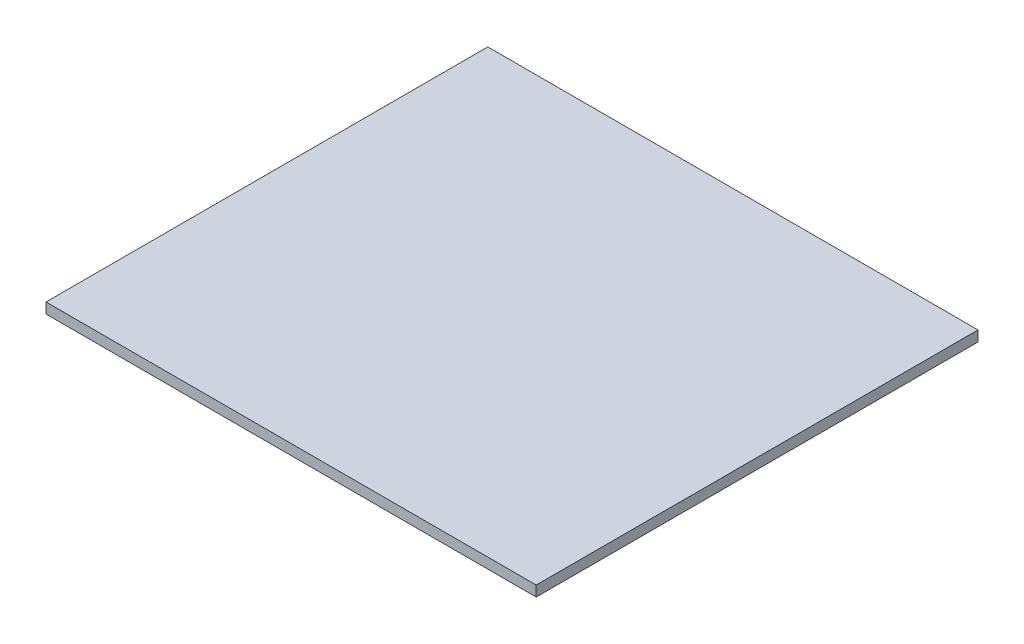
SolidWorks part; units mm, degrees
ref_plane "Front Plane" through (0, 0, 0) normal (0, 0, 1) x (1, 0, 0)
ref_plane "Top Plane" through (0, 0, 0) normal (0, 1, 0) x (1, 0, 0)
ref_plane "Right Plane" through (0, 0, 0) normal (1, 0, 0) x (0, 0, -1)
sketch "Sketch1" plane through (0, 0, 0) normal (0, 1, 0) x (1, 0, 0)
  line L1 (-41, 36.95) -> (41, 36.95)
  line L2 (-41, 36.95) -> (-41, -36.95)
  line L3 (-41, -36.95) -> (41, -36.95)
  line L4 (41, 36.95) -> (41, -36.95)
  line L5 (-41, 36.95) -> (41, -36.95) construction
  line L6 (-41, -36.95) -> (41, 36.95) construction
  point P0 (0, 0)
  dimension "D1" = 73.9
  dimension "D2" = 82
extrude "Boss-Extrude1" add sketch "Sketch1" along normal blind 1.75
sketch "Sketch2"
